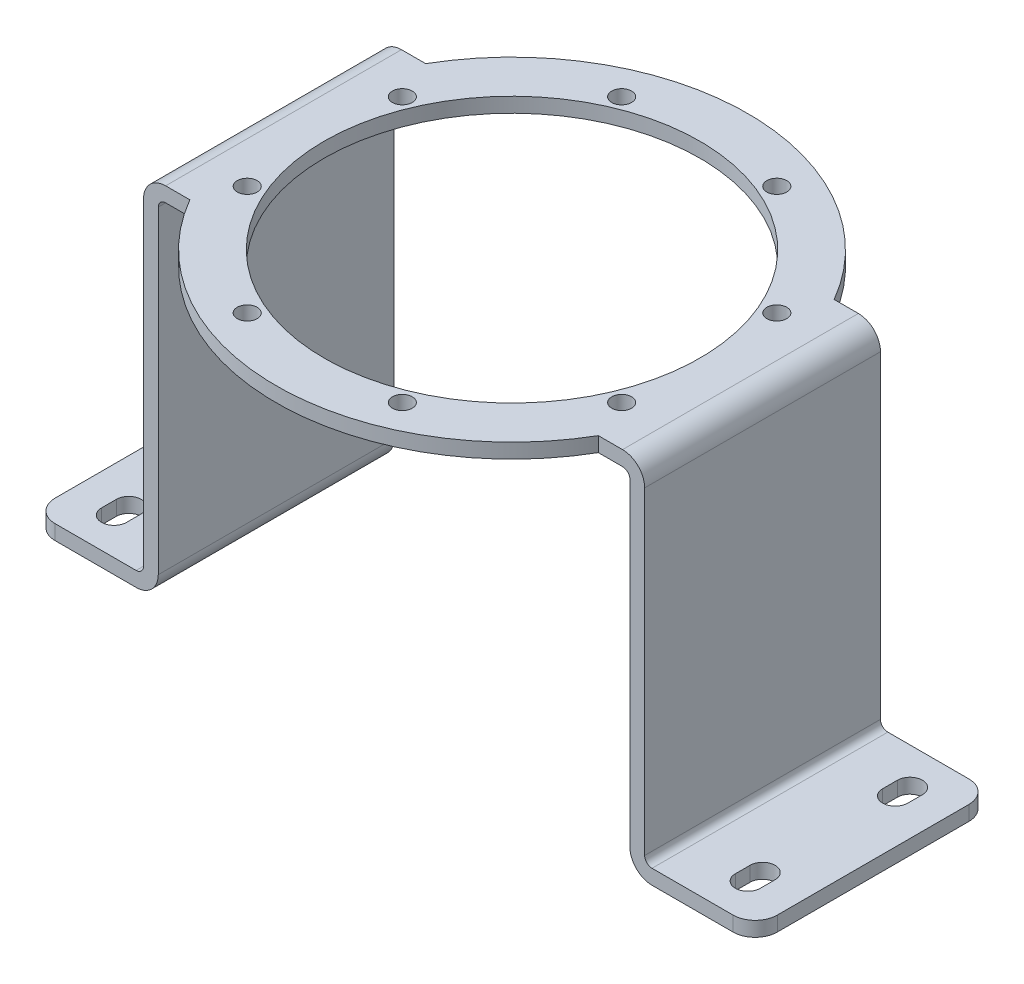
SolidWorks part; units mm, degrees
material "5052-H32"
ref_plane "Front Plane" through (0, 0, 0) normal (0, 0, 1) x (1, 0, 0)
ref_plane "Top Plane" through (0, 0, 0) normal (0, 1, 0) x (1, 0, 0)
ref_plane "Right Plane" through (0, 0, 0) normal (1, 0, 0) x (0, 0, -1)
other "Configuration Table"
sketch "草图1" plane through (0, 53.2, 0) normal (0, 1, 0) x (1, 0, 0)
  line L0 (0, 0) -> (-32, 0) construction
  line L1 (-34, 16) -> (-34, -16)
  line L2 (-34, -16) -> (-27.7128, -16)
  line L3 (-34, 16) -> (-27.7128, 16)
  line L4 (0, 32) -> (0, -32) construction
  line L5 (34, -16) -> (27.7128, -16)
  line L6 (34, 16) -> (34, -16)
  line L7 (34, 16) -> (27.7128, 16)
  circle A0 centre (0, 0) radius 25.5
  arc A1 (-27.7128, -16) -> (27.7128, -16) centre (0, 0) ccw
  arc A2 (27.7128, 16) -> (-27.7128, 16) centre (0, 0) ccw
  dimension "D1" = 51
  dimension "D2" = 64
  dimension "D3" = 2
  dimension "D4" = 32
  dimension "D5" = 34
extrude "凸台-拉伸1" add sketch "草图1" along normal blind 2
sketch "草图2" plane through (0, 53.2, 0) normal (0, -1, 0) x (1, 0, 0)
  line L0 (-34, 16) -> (-27.7128, 16) construction
  line L1 (-34, -16) -> (-32, -16)
  line L2 (-34, -16) -> (-34, 16)
  line L3 (-34, 16) -> (-32, 16)
  line L4 (-32, -16) -> (-32, 16)
  line L5 (0, 32) -> (0, -32) construction
  line L6 (34, 16) -> (32, 16)
  line L7 (32, -16) -> (32, 16)
  line L8 (34, -16) -> (34, 16)
  line L9 (34, -16) -> (32, -16)
  arc A0 (27.7128, 16) -> (-27.7128, 16) centre (0, 0) ccw construction
  arc A1 (-27.7128, -16) -> (27.7128, -16) centre (0, 0) ccw construction
  dimension "D1" = 2
extrude "凸台-拉伸2" add sketch "草图2" along normal blind 47.2
sketch "草图3" plane through (-34, 0, 0) normal (-1, 0, 0) x (0, 0, 1)
  line L0 (-16, 55.2) -> (-16, 6) construction
  line L1 (16, 6) -> (-16, 6)
  line L2 (16, 6) -> (16, 8)
  line L3 (16, 8) -> (-16, 8)
  line L4 (-16, 6) -> (-16, 8)
  dimension "D1" = 2
extrude "凸台-拉伸3" add sketch "草图3" along normal blind 15
ref_plane "基准面1" through (0, 0, 0) normal (-1, 0, 0) x (0, 0, 1)
mirror "镜向1" about plane through (0, 0, 0) normal (-1, 0, 0) of "凸台-拉伸3"
fillet "圆角1" radius 3 4 edges at (32, 6, 0) (-32, 6, 0) (34, 55.2, 0) (-34, 55.2, 0)
fillet "圆角2" radius 1 4 edges at (32, 53.2, 0) (34, 8, 0) (-34, 8, 0) (-32, 53.2, 0)
sketch "草图4" plane through (0, 55.2, 0) normal (0, 1, 0) x (1, 0, 0)
  line L1 (10.5238, -25.4067) -> (25.4067, -10.5238) construction
  line L2 (25.4067, -10.5238) -> (25.4067, 10.5238) construction
  line L3 (25.4067, 10.5238) -> (10.5238, 25.4067) construction
  line L4 (10.5238, 25.4067) -> (-10.5238, 25.4067) construction
  line L5 (-10.5238, 25.4067) -> (-25.4067, 10.5238) construction
  line L6 (-25.4067, 10.5238) -> (-25.4067, -10.5238) construction
  line L7 (-25.4067, -10.5238) -> (-10.5238, -25.4067) construction
  line L8 (-10.5238, -25.4067) -> (10.5238, -25.4067) construction
  circle A0 centre (0, 0) radius 27.5 construction
  circle A1 centre (-10.5238, 25.4067) radius 1.35
  circle A2 centre (10.5238, 25.4067) radius 1.35
  circle A3 centre (25.4067, 10.5238) radius 1.35
  circle A4 centre (25.4067, -10.5238) radius 1.35
  circle A5 centre (10.5238, -25.4067) radius 1.35
  circle A6 centre (-10.5238, -25.4067) radius 1.35
  circle A7 centre (-25.4067, -10.5238) radius 1.35
  circle A8 centre (-25.4067, 10.5238) radius 1.35
  point P28 (0, 0)
  dimension "D1" = 55
  dimension "D2" = 2.7
  dimension "D3" = 8
extrude "切除-拉伸1" cut sketch "草图4" against normal blind 10
sketch "草图6" plane through (0, 8, 0) normal (0, 1, 0) x (1, 0, 0)
  line L0 (-43, 10) -> (-43, -10) construction
  line L2 (-43, 11) -> (-43, 9) construction
  line L3 (-49, 0) -> (-35, 0) construction
  line L4 (-49, -16) -> (-49, 16) construction
  line L5 (-35, -16) -> (-35, 16) construction
  line L6 (-41.3, 11) -> (-41.3, 9)
  line L7 (-44.7, 11) -> (-44.7, 9)
  line L8 (-49, 16) -> (-35, 16) construction
  line L9 (-43, -11) -> (-43, -9) construction
  line L10 (-41.3, -11) -> (-41.3, -9)
  line L11 (-44.7, -11) -> (-44.7, -9)
  arc A2 (-41.3, 11) -> (-44.7, 11) centre (-43, 11) ccw
  arc A3 (-44.7, 9) -> (-41.3, 9) centre (-43, 9) ccw
  arc A4 (-41.3, -11) -> (-44.7, -11) centre (-43, -11) cw
  arc A5 (-44.7, -9) -> (-41.3, -9) centre (-43, -9) cw
  point P4 (-43, 10)
  point P21 (-43, -10)
  dimension "D1" = 6
  dimension "D2" = 1.7
  dimension "D3" = 2
  dimension "D5" = 6
extrude "切除-拉伸2" cut sketch "草图6" against normal blind 10
mirror "镜向2" about plane through (0, 0, 0) normal (-1, 0, 0) of "切除-拉伸2"
fillet "圆角3" radius 3 4 edges at (49, 7, 16) (49, 7, -16) (-49, 7, -16) (-49, 7, 16)
